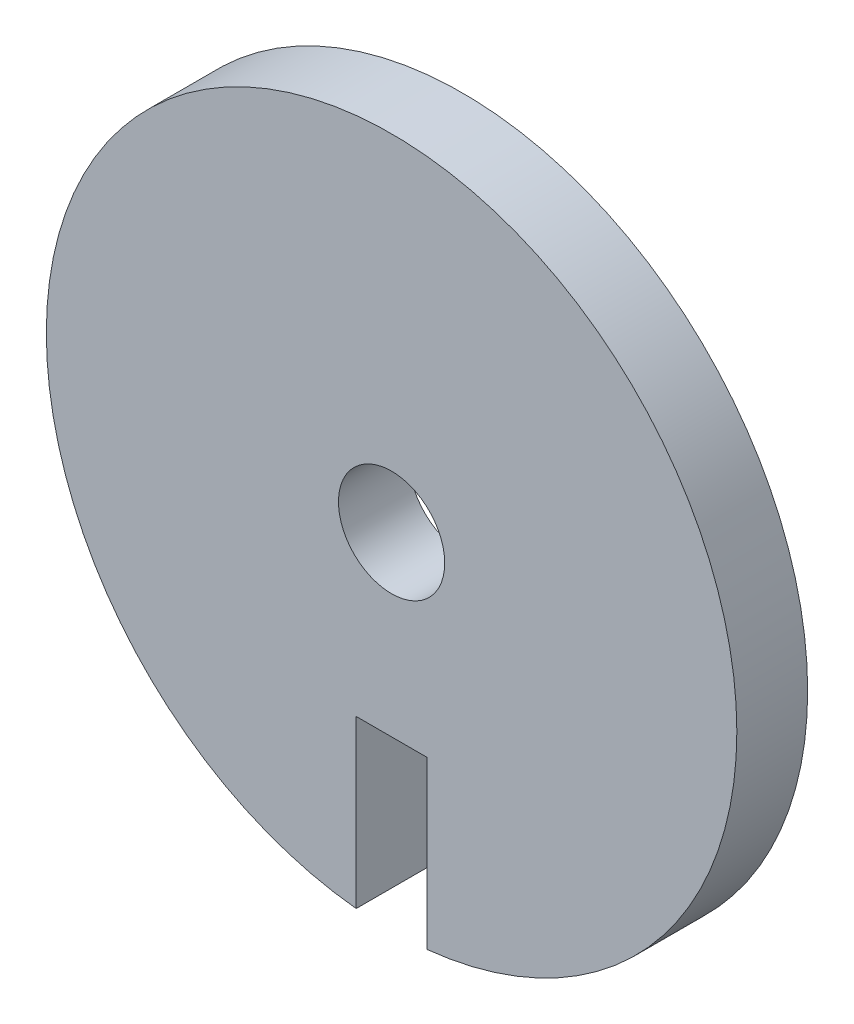
SolidWorks part; units mm, degrees
ref_plane "Vorne" through (0, 0, 0) normal (0, 0, 1) x (1, 0, 0)
ref_plane "Oben" through (0, 0, 0) normal (0, 1, 0) x (1, 0, 0)
ref_plane "Rechts" through (0, 0, 0) normal (1, 0, 0) x (0, 0, -1)
sketch "Skizze1" plane through (0, 0, 0) normal (0, 0, 1) x (1, 0, 0)
  circle A0 centre (0, 0) radius 19.5
  dimension "D1" = 39
extrude "Aufsatz-Linear austragen1" add sketch "Skizze1" along normal blind 4
sketch "Skizze4" plane through (0, 0, 4) normal (0, 0, 1) x (1, 0, 0)
  circle A0 centre (0, 0) radius 3
  dimension "D1" = 6
extrude "Schnitt-Linear austragen2" cut sketch "Skizze4" against normal blind 4
sketch "Skizze6" plane through (0, 0, 4) normal (0, 0, 1) x (1, 0, 0)
  line L1 (-2, -20) -> (2, -20)
  line L2 (-2, -20) -> (-2, -10)
  line L3 (-2, -10) -> (2, -10)
  line L4 (2, -20) -> (2, -10)
  dimension "D1" = 4
  dimension "D2" = 2
  dimension "D3" = 10
  dimension "D4" = 10
extrude "Schnitt-Linear austragen3" cut sketch "Skizze6" against normal blind 4
